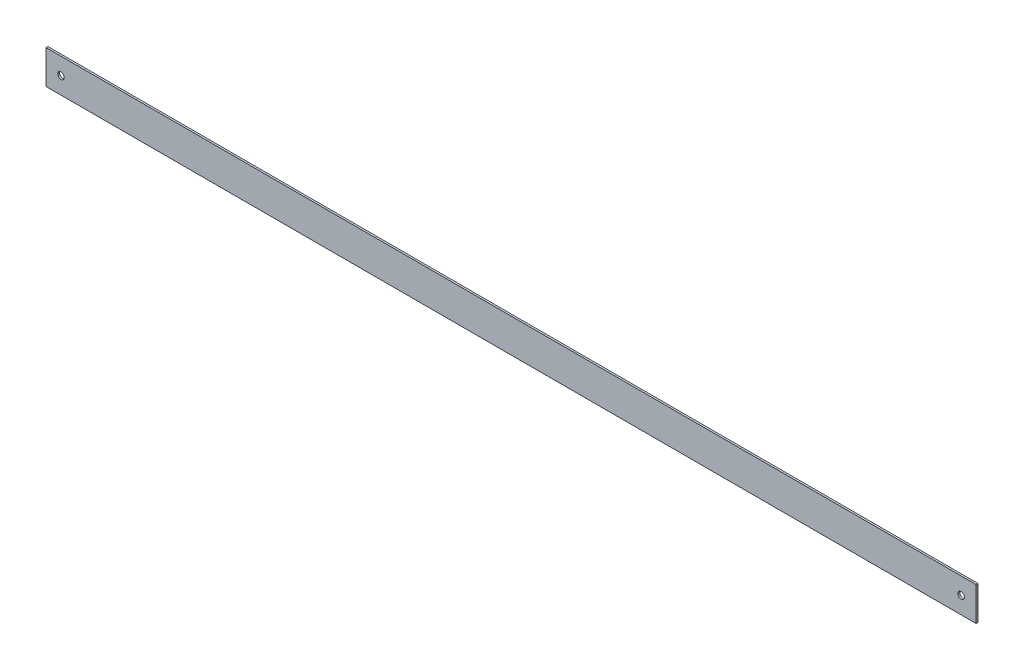
SolidWorks part; units mm, degrees
material "AISI 316 Stainless Steel Sheet (SS)"
ref_plane "Front Plane" through (0, 0, 0) normal (0, 0, 1) x (1, 0, 0)
ref_plane "Top Plane" through (0, 0, 0) normal (0, 1, 0) x (1, 0, 0)
ref_plane "Right Plane" through (0, 0, 0) normal (1, 0, 0) x (0, 0, -1)
sketch "Sketch1" plane through (0, 0, 0) normal (0, 0, 1) x (1, 0, 0)
  line L0 (0, 0) -> (0, 28.575)
  line L1 (0, 28.575) -> (787.4, 28.575)
  line L2 (787.4, 28.575) -> (787.4, 0)
  line L3 (787.4, 0) -> (0, 0)
  dimension "D1" = 787.4
  dimension "D2" = 28.575
  dimension "D3" = 0
extrude "Boss-Extrude1" add sketch "Sketch1" along normal blind 1.5875
sketch "Sketch2" plane through (0, 0, 1.5875) normal (0, 0, 1) x (1, 0, 0)
  line L0 (0, 28.575) -> (0, 0) construction
  line L1 (787.4, 28.575) -> (0, 28.575) construction
  point P0 (12.7, 14.2875)
  dimension "D1" = 12.7
  dimension "D2" = 14.2875
hole_wizard "M5 Clearance Hole1" positions "Sketch3" profile "Sketch4" hole size "M5" standard "ANSI Metric" end condition through all
sketch "Sketch3" plane through (0, 0, 1.5875) normal (0, 0, 1) x (1, 0, 0)
  point P0 (12.7, 14.2875)
sketch "Sketch4" plane through (12.7, 14.2875, 1.5875) normal (1, 0, 0) x (0, -1, 0)
  line L0 (0, 0) -> (0, 1.5875)
  line L1 (0, 1.5875) -> (2.75, 1.5875)
  line L2 (2.75, 1.5875) -> (2.75, 0)
  line L5 (2.75, 0) -> (0, 0)
  line L11 (0, -6.35) -> (0, 107.95) construction
  dimension "Thru Hole Dia." = 5.5
  dimension "Thru Hole Depth" = 1.5875
ref_plane "Plane1" through (393.7, 0, 0) normal (1, 0, 0) x (0, 0, -1)
mirror "Mirror1" about plane through (393.7, 0, 0) normal (1, 0, 0) of "M5 Clearance Hole1"
